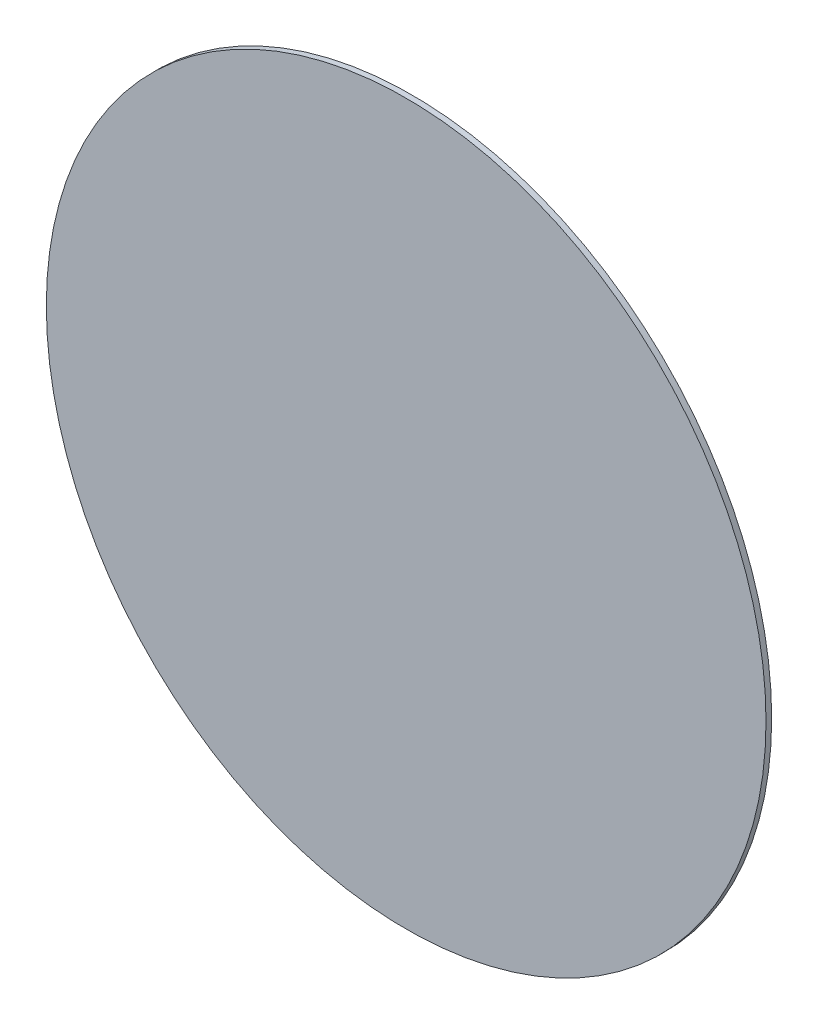
SolidWorks part; units mm, degrees
ref_plane "Front Plane" through (0, 0, 0) normal (0, 0, 1) x (1, 0, 0)
ref_plane "Top Plane" through (0, 0, 0) normal (0, 1, 0) x (1, 0, 0)
ref_plane "Right Plane" through (0, 0, 0) normal (1, 0, 0) x (0, 0, -1)
sketch "Sketch2" plane through (0, 0, 0) normal (0, 0, 1) x (1, 0, 0)
  circle A0 centre (0, 0) radius 63.5
  dimension "D1" = 127
extrude "Boss-Extrude1" add sketch "Sketch2" along normal blind 1
